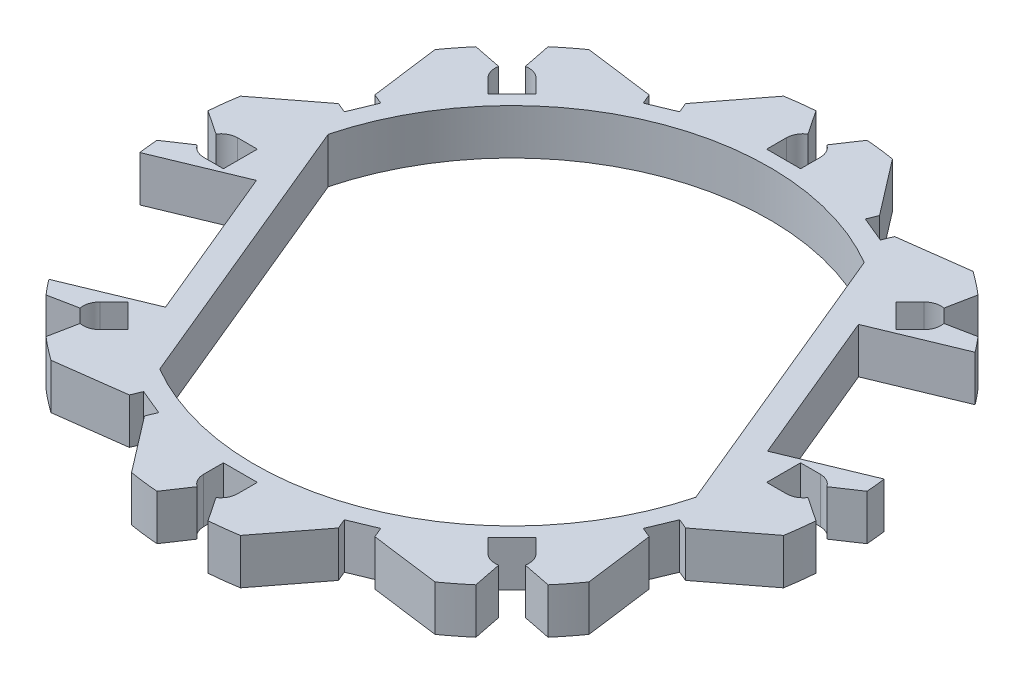
SolidWorks part; units mm, degrees
ref_plane "Front Plane" through (0, 0, 0) normal (0, 0, 1) x (1, 0, 0)
ref_plane "Top Plane" through (0, 0, 0) normal (0, 1, 0) x (1, 0, 0)
ref_plane "Right Plane" through (0, 0, 0) normal (1, 0, 0) x (0, 0, -1)
sketch "Sketch1" plane through (0, 0, 0) normal (0, 1, 0) x (1, 0, 0)
  circle A0 centre (0, 0) radius 54.55
extrude "Boss-Extrude1" add sketch "Sketch1" along normal blind 7.5
sketch "Sketch2" plane through (0, 7.5, 0) normal (0, 1, 0) x (1, 0, 0)
  circle A0 centre (0, 0) radius 42.5
extrude "Cut-Extrude1" cut sketch "Sketch2" against normal through all
sketch "Sketch3" plane through (0, 7.5, 0) normal (0, 1, 0) x (1, 0, 0)
  line L2 (-2.8, -48.082) -> (-2.8, -44.832)
  line L3 (-2.8, -44.832) -> (2.8, -44.832)
  line L4 (2.8, -48.082) -> (2.8, -44.832)
  line L7 (-1.5556, -50.4101) -> (-4.2129, -54.3871)
  line L8 (1.5556, -50.4101) -> (4.2129, -54.3871)
  circle A1 centre (0, 0) radius 54.55 construction
  arc A2 (-2.8, -48.082) -> (-1.5556, -50.4101) centre (0, -48.082) ccw
  arc A3 (1.5556, -50.4101) -> (2.8, -48.082) centre (0, -48.082) ccw
  arc A4 (-4.2129, -54.3871) -> (4.2129, -54.3871) centre (0, 0) ccw
  dimension "D1" = 5.6
  dimension "D2" = 3.25
  dimension "D4" = 3.25
  dimension "D6" = 67.5
extrude "Cut-Extrude2" cut sketch "Sketch3" against normal through all
sketch "Sketch4" plane through (0, 7.5, 0) normal (0, 1, 0) x (-1, 0, 0)
  line L0 (2.75, 48.082) -> (-2.75, 48.082)
  line L1 (2.75, 48.082) -> (2.75, 44.882)
  line L2 (-2.75, 48.082) -> (-2.75, 44.882)
  line L3 (2.75, 44.882) -> (-2.75, 44.882)
  line L4 (2.75, 48.082) -> (-2.75, 44.882) construction
  line L5 (-2.75, 48.082) -> (2.75, 44.882) construction
  line L6 (-2.8, 44.832) -> (2.8, 44.832) construction
  line L7 (0, 0) -> (0, 46.482)
  line L8 (0, 0) -> (20.8754, 50.3976) construction
  arc A0 (-2.1, 48.082) -> (2.1, 48.082) centre (0, 48.082) cw
  point P1 (0, 46.482)
  dimension "D4" = 2.1
  dimension "D1" = 46.482
  dimension "D2" = 5.5
  dimension "D3" = 3.2
  dimension "D5" = 0.05
  dimension "D6" = 22.5
ref_axis "Axis1" through (0, 10.8722, 0) along (0, -1, 0)
sketch "Sketch7" plane through (0, 7.5, 0) normal (0, 1, 0) x (1, 0, 0)
  line L0 (0, 0) -> (-20.8754, -50.3976)
  line L1 (-20.1919, -42.868) -> (-16.0344, -44.5901)
  line L2 (-20.1919, -42.868) -> (-19.5413, -41.2974)
  line L3 (-16.0344, -44.5901) -> (-15.3839, -43.0195)
  line L4 (-19.5413, -41.2974) -> (-15.3839, -43.0195)
  line L5 (-20.1919, -42.868) -> (-15.3839, -43.0195) construction
  line L6 (-16.0344, -44.5901) -> (-19.5413, -41.2974) construction
  line L7 (0, 0) -> (0, -46.482) construction
  arc A1 (-16.7259, -44.3037) -> (-19.5004, -43.1544) centre (-18.1132, -43.7291) cw
  point P7 (-17.7879, -42.9438)
  dimension "D1" = 46.482
  dimension "D2" = 4.5
  dimension "D3" = 1.7
  dimension "D4" = 22.5
sketch "Sketch9" plane through (0, 7.5, 0) normal (0, 1, 0) x (1, 0, 0)
  line L4 (-20.2572, -42.8951) -> (-31.6909, -44.4004)
  line L5 (-16.0074, -44.6554) -> (-8.987, -53.8046)
  line L6 (0, 0) -> (-20.8754, -50.3976) construction
  line L8 (-19.5684, -41.2321) -> (-20.2572, -42.8951)
  line L9 (-20.2572, -42.8951) -> (-16.0074, -44.6554)
  line L10 (-16.0074, -44.6554) -> (-15.3186, -42.9924)
  line L11 (-15.3186, -42.9924) -> (-19.5684, -41.2321)
  line L12 (-19.5684, -41.2321) -> (-20.2572, -42.8951)
  line L14 (-16.0074, -44.6554) -> (-15.3186, -42.9924)
  line L15 (-15.3186, -42.9924) -> (-19.5684, -41.2321)
  arc A0 (4.2129, -54.3871) -> (-4.2129, -54.3871) centre (0, 0) ccw construction
  arc A1 (-31.6909, -44.4004) -> (-8.987, -53.8046) centre (0, 0) ccw
  dimension "D2" = 60
  dimension "D3" = 60
  dimension "D1" = 0.05
extrude "Cut-Extrude6" cut sketch "Sketch9" against normal through all
pattern_circular "CirPattern1" count 8 over 360 about axis through (0, 0, 0) along (0, 1, 0) of "Cut-Extrude2"
pattern_circular "CirPattern2" count 8 over 360 about axis through (0, 10.8722, 0) along (0, -1, 0) skipping 1, 5 of "Cut-Extrude6"
ref_plane "Plane1" through (0, 0, 0) normal (0.9239, 0, -0.3827) x (-0.3827, 0, -0.9239)
sketch "Sketch10" plane through (0, 0, 0) normal (0, -1, 0) x (1, 0, 0)
  line L0 (-42.4228, 2.5598) -> (-31.8075, 28.1874)
  line L1 (-42.4228, 2.5598) -> (-56.6716, 8.4618)
  line L2 (-31.8075, 28.1874) -> (-46.0563, 34.0895)
  line L3 (-56.6716, 8.4618) -> (-46.0563, 34.0895)
  circle A0 centre (0, 0) radius 42.5 construction
  dimension "D1" = 0.7
  dimension "D2" = 0.7
extrude "Cut-Extrude7" cut sketch "Sketch10" against normal through all
sketch "Sketch11" plane through (0, 0, 0) normal (0, -1, 0) x (1, 0, 0)
  line L0 (-42.4228, 2.5598) -> (-40.4428, 1.7396)
  line L1 (-31.8075, 28.1874) -> (-29.8275, 27.3673)
  line L2 (-41.111, -10.7764) -> (-21.4498, 36.69)
  line L3 (-29.8275, 27.3673) -> (-40.4428, 1.7396)
  arc A0 (-42.4228, 2.5598) -> (-31.8075, 28.1874) centre (0, 0) ccw construction
  arc A1 (-42.4228, 2.5598) -> (-41.111, -10.7764) centre (0, 0) ccw
  arc A2 (-21.4498, 36.69) -> (-31.8075, 28.1874) centre (0, 0) ccw
extrude "Boss-Extrude2" add sketch "Sketch11" against normal through all
mirror "Mirror1" about plane through (0, 0, 0) normal (0.9239, 0, -0.3827) of "Boss-Extrude2", "Cut-Extrude7"
